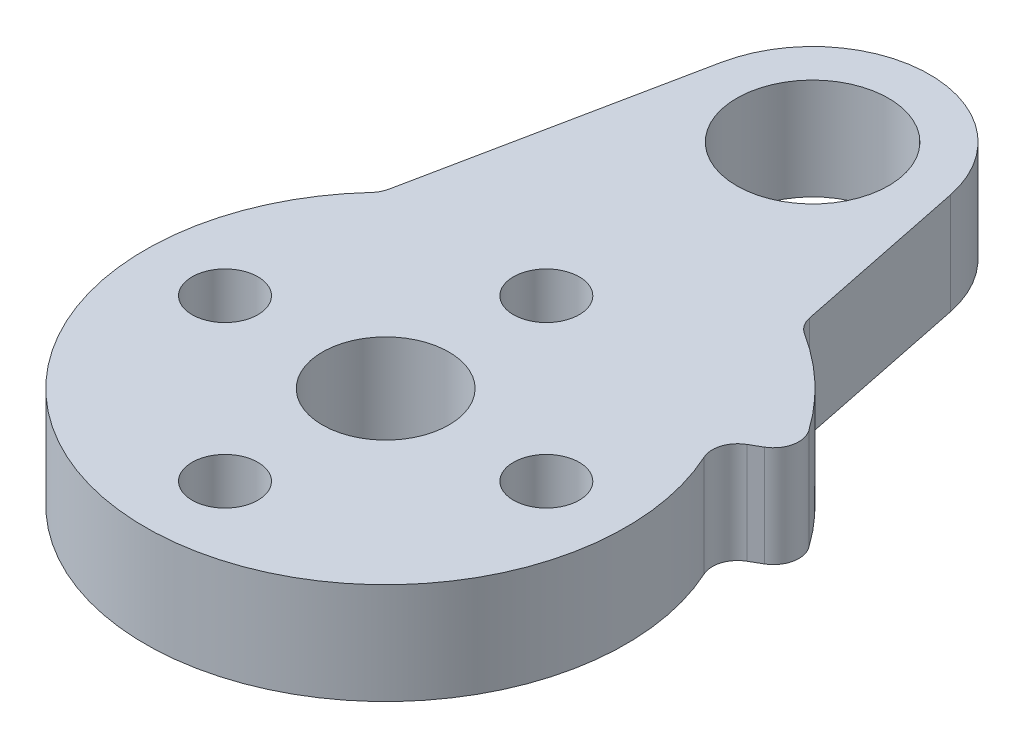
SolidWorks part; units mm, degrees
material "Tough 2000"
ref_plane "Front Plane" through (0, 0, 0) normal (0, 0, 1) x (1, 0, 0)
ref_plane "Top Plane" through (0, 0, 0) normal (0, 1, 0) x (1, 0, 0)
ref_plane "Right Plane" through (0, 0, 0) normal (1, 0, 0) x (0, 0, -1)
sketch "Sketch1" plane through (0, 0, 0) normal (0, 1, 0) x (1, 0, 0)
  line L1 (-4.5316, 17.7996) -> (-7.8384, 1.6)
  line L2 (4.5316, 17.7996) -> (7.8384, 1.6)
  arc A0 (-7.8384, 1.6) -> (7.8384, 1.6) centre (0, 0) ccw
  arc A1 (4.5316, 17.7996) -> (-4.5316, 17.7996) centre (0, 16.8746) ccw
  circle A2 centre (0, 16.8746) radius 3
  circle A3 centre (0, 0) radius 2.5
extrude "Boss-Extrude1" add sketch "Sketch1" along normal blind 4
sketch "Sketch2" plane through (0, 4, 0) normal (0, 1, 0) x (1, 0, 0)
  line L0 (0, 0) -> (0, 6.35) construction
  circle A0 centre (0, 6.35) radius 1.3
  circle A1 centre (6.35, 0) radius 1.3
  circle A2 centre (0, -6.35) radius 1.3
  circle A3 centre (-6.35, 0) radius 1.3
  point P13 (0, 0)
  dimension "D1" = 4
extrude "Cut-Extrude1" cut sketch "Sketch2" against normal blind 4
sketch "Sketch3" plane through (0, 4, 0) normal (0, 1, 0) x (1, 0, 0)
  line L0 (-7.8384, 1.6) -> (-6.8137, 6.62)
  line L1 (6.8137, 6.62) -> (7.8384, 1.6)
  line L2 (7.8384, 1.6) -> (4.5316, 17.7996) construction
  arc A1 (-6.8137, 6.62) -> (6.8137, 6.62) centre (0, 0) ccw
  arc A2 (-7.8384, 1.6) -> (7.8384, 1.6) centre (0, 0) ccw construction
  arc A3 (-7.8384, 1.6) -> (7.8384, 1.6) centre (0, 0) ccw
extrude "Boss-Extrude2" add sketch "Sketch3" against normal blind 4
sketch "Sketch4" plane through (0, 4, 0) normal (0, 1, 0) x (1, 0, 0)
  line L1 (8.2272, 4.75) -> (10.3923, 6)
  line L2 (0, 12) -> (0, 9.5)
  arc A0 (10.3923, 6) -> (0, 12) centre (0, 0) ccw
  arc A1 (8.2272, 4.75) -> (0, 9.5) centre (0, 0) ccw
extrude "Boss-Extrude3" add sketch "Sketch4" against normal up to surface (4 mm away) up to face at (0, 0, -9.1048)
fillet "Fillet1" radius 1 4 edges at (6.0495, 2, -10.3636) (8.2272, 2, -4.75) (10.3923, 2, -6) (-6.8137, 2, -6.62)
